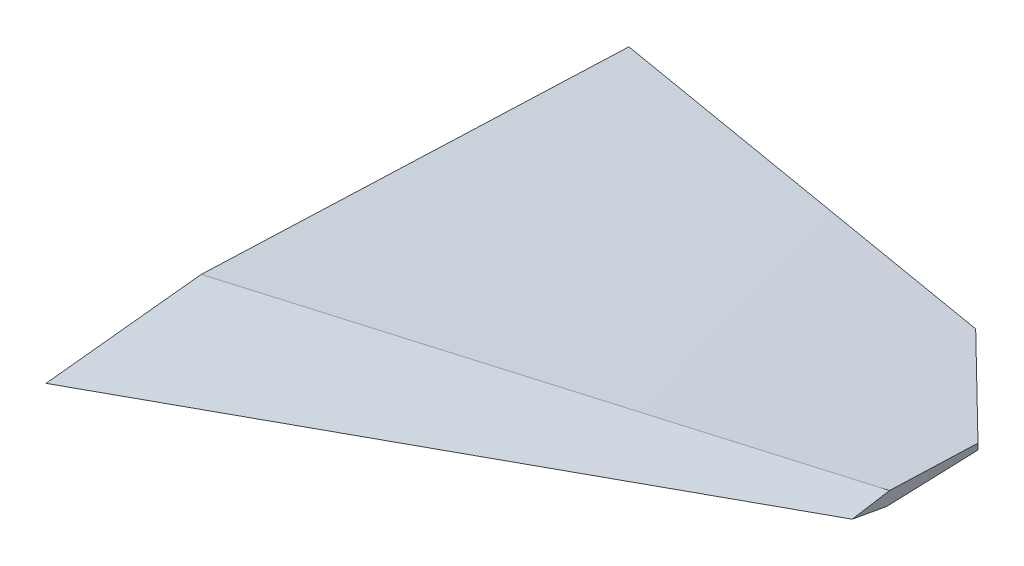
SolidWorks part; units mm, degrees
ref_plane "Front Plane" through (0, 0, 0) normal (0, 0, 1) x (1, 0, 0)
ref_plane "Top Plane" through (0, 0, 0) normal (0, 1, 0) x (1, 0, 0)
ref_plane "Right Plane" through (0, 0, 0) normal (1, 0, 0) x (0, 0, -1)
ref_plane "Plane1" through (1079.9992, 0, 0) normal (1, 0, 0) x (0, 0, -1)
sketch "Sketch1" plane through (1079.9992, 0, 0) normal (1, 0, 0) x (0, 0, -1)
  line L0 (4952.5, 1865) -> (7392.5, 1865) construction
  line L1 (5602.5, 1795) -> (5602.5, 1935) construction
  line L2 (-7407.5, -1516.8229) -> (-7407.5, 1516.8229) construction
  line L3 (4952.5, 1865) -> (5602.5, 1935)
  line L4 (5602.5, 1935) -> (7392.5, 1865)
  line L5 (5602.5, 1795) -> (7392.5, 1865)
  line L6 (4952.5, 1865) -> (5602.5, 1795)
  point P7 (5602.5, 1865)
  dimension "D1" = 2440
  dimension "D2" = 1865
  dimension "D3" = 650
  dimension "D4" = 13010
  dimension "D5" = 140
sketch "Sketch2" plane through (0, 0, 0) normal (0, 0, 1) x (1, 0, 0)
  line L0 (1079.9992, 1865) -> (2914.9992, 1520)
  dimension "D1" = 1835
  dimension "D2" = 345
ref_plane "Plane2" through (2914.9992, 1520, 0) normal (0.9828, -0.1848, 0) x (0, 0, -1)
sketch "Sketch3" plane through (2914.9992, 1520, 0) normal (0.9828, -0.1848, 0) x (0, 0, -1)
  line L0 (6492.5, 0) -> (7367.5, 0) construction
  line L1 (-7407.5, -3549.2649) -> (-7407.5, -515.6192) construction
  line L2 (6642.5, -32.5) -> (6642.5, 32.5) construction
  line L3 (6492.5, 0) -> (6642.5, 32.5)
  line L4 (6642.5, 32.5) -> (7367.5, 0)
  line L5 (6642.5, -32.5) -> (7367.5, 0)
  line L6 (6492.5, 0) -> (6642.5, -32.5)
  line L7 (4952.5, 0) -> (7392.5, 0) construction
  point P7 (6642.5, 0)
  dimension "D1" = 13900
  dimension "D2" = 875
  dimension "D3" = 65
  dimension "D4" = 150
loft "Loft1" add profiles "Sketch1", "Sketch3"
sketch "Sketch4" plane through (0, 0, 0) normal (0, 1, 0) x (1, 0, 0)
  line L0 (2264, 7652.5) -> (4524, 5452.5)
  line L1 (0, -245.8173) -> (0, 245.8173) construction
  line L2 (1516.8229, -7407.5) -> (-1516.8229, -7407.5) construction
  dimension "D1" = 2264
  dimension "D2" = 2260
  dimension "D3" = 2200
  dimension "D4" = 12860
split "Split1" trim tools "Sketch4" bodies to split 101 resulting bodies 103
